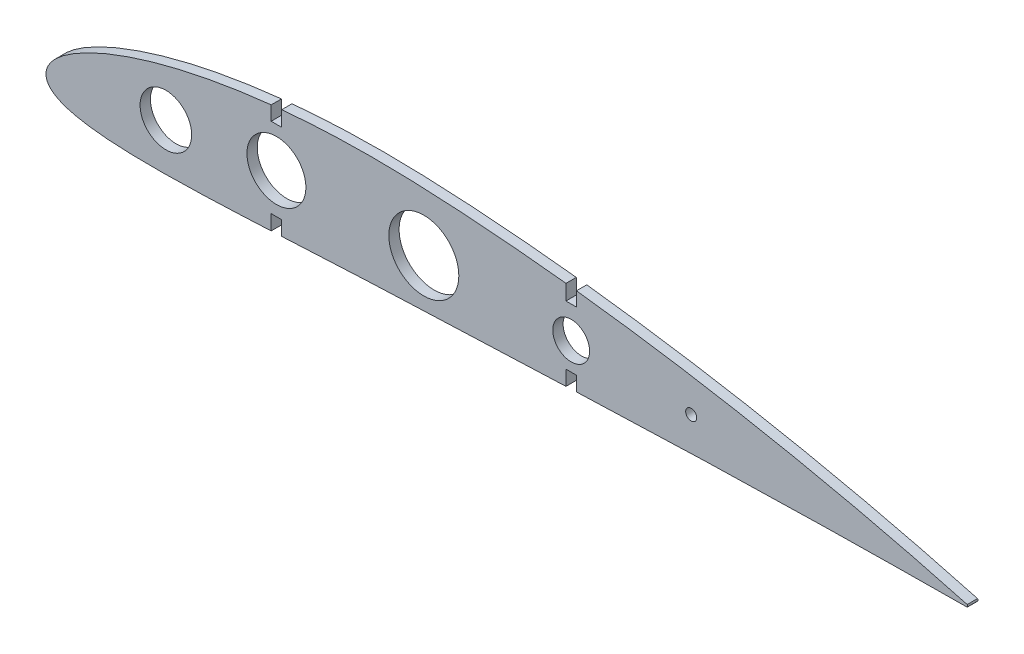
SolidWorks part; units mm, degrees
material "Фанера"
ref_plane "Front Plane" through (0, 0, 0) normal (0, 0, 1) x (1, 0, 0)
ref_plane "Top Plane" through (0, 0, 0) normal (0, 1, 0) x (1, 0, 0)
ref_plane "Right Plane" through (0, 0, 0) normal (1, 0, 0) x (0, 0, -1)
curve "Кривая5"
  spline degree 3 poles (0.048, 0.6214, 0) (0.0227, 0.3735, 0) (-0.0278, -0.1225, 0) (0.078, -0.8844, 0) (0.3497, -1.6388, 0) (0.8143, -2.3651, 0) (1.4635, -3.0393, 0) (2.291, -3.661, 0) (3.3059, -4.2358, 0) (4.5353, -4.7737, 0) (6.0297, -5.2822, 0) (7.869, -5.7653, 0) (10.1688, -6.2217, 0) (13.0754, -6.6396, 0) (16.7281, -6.993, 0) (21.19, -7.2473, 0) (26.4, -7.3766, 0) (32.1974, -7.3763, 0) (38.3978, -7.2614, 0) (44.8576, -7.0566, 0) (51.4865, -6.7865, 0) (58.231, -6.4723, 0) (65.0521, -6.1329, 0) (71.9108, -5.784, 0) (78.7714, -5.4397, 0) (85.6105, -5.111, 0) (92.4321, -4.805, 0) (99.255, -4.532, 0) (106.0974, -4.2783, 0) (112.9692, -4.0031, 0) (119.8644, -3.7232, 0) (126.7739, -3.4401, 0) (133.6816, -3.1587, 0) (140.5819, -2.8824, 0) (147.472, -2.6139, 0) (154.3526, -2.3556, 0) (161.225, -2.1094, 0) (168.0909, -1.8766, 0) (174.9516, -1.6586, 0) (181.8086, -1.4564, 0) (188.6632, -1.2704, 0) (195.5166, -1.1011, 0) (202.3695, -0.9486, 0) (209.2212, -0.8129, 0) (216.0668, -0.6936, 0) (222.8864, -0.5903, 0) (229.6176, -0.5029, 0) (236.0874, -0.4315, 0) (241.9808, -0.3765, 0) (246.559, -0.3395, 0) (249.1205, -0.3213, 0) (250, -0.315, 0) knots 0 0 0 0 0.002941 0.005884 0.009016 0.012365 0.016008 0.020037 0.024574 0.029784 0.035897 0.04324 0.052276 0.063635 0.077983 0.095698 0.11652 0.139661 0.164312 0.189919 0.216157 0.242838 0.269834 0.296993 0.324123 0.351139 0.378036 0.404946 0.431961 0.459078 0.486347 0.513641 0.540929 0.568176 0.59538 0.622543 0.649673 0.676775 0.703855 0.730919 0.757971 0.785018 0.812062 0.839103 0.866132 0.893099 0.919831 0.94581 0.969681 0.98959 1 1 1 1
curve "Кривая6"
  spline degree 3 poles (250, 0.315, 0) (249.1557, 0.545, 0) (246.7202, 1.2085, 0) (242.3913, 2.3583, 0) (236.8498, 3.7876, 0) (230.7799, 5.298, 0) (224.4559, 6.8129, 0) (218.0305, 8.2916, 0) (211.5624, 9.7197, 0) (205.0724, 11.0924, 0) (198.568, 12.4079, 0) (192.0524, 13.6653, 0) (185.5276, 14.8641, 0) (178.9953, 16.0034, 0) (172.4571, 17.0824, 0) (165.9143, 18.0998, 0) (159.3687, 19.0545, 0) (152.8218, 19.9449, 0) (146.2754, 20.7693, 0) (139.7314, 21.5257, 0) (133.1918, 22.212, 0) (126.6587, 22.8257, 0) (120.1368, 23.364, 0) (113.6286, 23.8247, 0) (107.1527, 24.2002, 0) (100.7411, 24.4984, 0) (94.4118, 24.6866, 0) (88.1559, 24.7401, 0) (81.949, 24.6588, 0) (75.7805, 24.441, 0) (69.6537, 24.0819, 0) (63.5754, 23.578, 0) (57.5552, 22.9249, 0) (51.6058, 22.1191, 0) (45.7444, 21.1566, 0) (39.9959, 20.0354, 0) (34.3979, 18.7563, 0) (29.0104, 17.3276, 0) (23.9258, 15.7719, 0) (19.2707, 14.1343, 0) (15.1791, 12.4833, 0) (11.7405, 10.8956, 0) (8.9594, 9.4296, 0) (6.7609, 8.1086, 0) (5.0337, 6.9246, 0) (3.6717, 5.8542, 0) (2.5921, 4.8713, 0) (1.7382, 3.9526, 0) (1.0699, 3.0809, 0) (0.5716, 2.2416, 0) (0.2158, 1.4308, 0) (0.1023, 0.8832, 0) (0.048, 0.6214, 0) knots 0 0 0 0 0.010162 0.029313 0.052012 0.076619 0.101948 0.127526 0.153184 0.178868 0.204558 0.230246 0.255926 0.281594 0.307246 0.332878 0.358485 0.384061 0.409603 0.435104 0.460559 0.485959 0.511303 0.536552 0.561723 0.586629 0.611085 0.635251 0.659272 0.683164 0.706922 0.730536 0.753983 0.777235 0.800246 0.822951 0.845237 0.866916 0.887662 0.906968 0.924203 0.938879 0.950932 0.960693 0.968647 0.975233 0.980795 0.985584 0.989782 0.993521 0.996902 1 1 1 1
sketch "Эскиз1" plane through (0, 0, 0) normal (0, 0, 1) x (1, 0, 0)
  line L0 (250.1305, 0) -> (250.1305, 54.8427) construction
  line L1 (0, 0) -> (0, 70.5199) construction
  line L2 (0, 0) -> (253.0634, 0) construction
  line L3 (62.5326, 62.6361) -> (62.5326, -41.5636) construction
  line L4 (142.5326, 67.9319) -> (142.5326, 25.1988) construction
  line L5 (175.0913, 63.8571) -> (175.0913, -32.3947) construction
  line L6 (32.5326, -14.3434) -> (32.5326, 29.5903) construction
  line L7 (142.5326, 21.1988) -> (142.5326, -57.0034) construction
  line L8 (61.1076, 19.4501) -> (63.9576, 19.4501)
  line L9 (61.1076, 19.4501) -> (61.1076, 23.3031)
  line L11 (63.9576, 19.4501) -> (63.9576, 23.5885)
  line L12 (61.1076, 19.4501) -> (62.5326, 23.4501) construction
  line L13 (62.5326, 23.4501) -> (63.9576, 19.4501) construction
  line L15 (61.1076, -6.3284) -> (61.1076, -2.2577)
  line L16 (61.1076, -2.2577) -> (63.9576, -2.2577)
  line L17 (63.9576, -6.1866) -> (63.9576, -2.2577)
  line L18 (62.5326, -6.2577) -> (63.9576, -2.2577) construction
  line L19 (61.1076, -2.2577) -> (62.5326, -6.2577) construction
  line L20 (141.1076, 17.1988) -> (143.9576, 17.1988)
  line L21 (141.1076, 17.1988) -> (141.1076, 21.3608)
  line L23 (143.9576, 17.1988) -> (143.9576, 21.0336)
  line L24 (141.1076, 17.1988) -> (142.5326, 21.1988) construction
  line L25 (142.5326, 21.1988) -> (143.9576, 17.1988) construction
  line L28 (141.1076, -2.8629) -> (141.1076, 1.1931)
  line L29 (141.1076, 1.1931) -> (143.9576, 1.1931)
  line L30 (143.9576, -2.7512) -> (143.9576, 1.1931)
  line L31 (142.5326, -2.8069) -> (143.9576, 1.1931) construction
  line L32 (141.1076, 1.1931) -> (142.5326, -2.8069) construction
  arc A0 (250, 0.315) -> (250, -0.315) centre (249.685, 0) cw
  circle A1 centre (62.5326, 8.5962) radius 8
  circle A2 centre (142.5326, 8.5962) radius 5
  circle A3 centre (32.5326, 5.4481) radius 7
  circle A5 centre (102.5326, 8.5962) radius 9.5
  circle A6 centre (175.0913, 7.4939) radius 1.5
  arc A7 (175.0913, 16.6448) -> (175.0913, -1.657) centre (175.0913, 7.4939) ccw
  spline S2 degree 3 poles (0.048, 0.6214) (0.0227, 0.3735) (-0.0278, -0.1225) (0.078, -0.8844) (0.3497, -1.6388) (0.8143, -2.3651) (1.4635, -3.0393) (2.291, -3.661) (3.3059, -4.2358) (4.5353, -4.7737) (6.0297, -5.2822) (7.869, -5.7653) (10.1688, -6.2217) (13.0754, -6.6396) (16.7281, -6.993) (21.19, -7.2473) (26.4, -7.3766) (32.1974, -7.3763) (38.3978, -7.2614) (44.8576, -7.0566) (51.4865, -6.7865) (56.9206, -6.5334) (60.1398, -6.3761) (61.1076, -6.3284) knots 0 0 0 0 0.002941 0.005884 0.009016 0.012365 0.016008 0.020037 0.024574 0.029784 0.035897 0.04324 0.052276 0.063635 0.077983 0.095698 0.11652 0.139661 0.164312 0.189919 0.216157 0.242838 0.254307 0.254307 0.254307 0.254307
  spline S3 degree 3 poles (250, 0.315) (249.1557, 0.545) (246.7202, 1.2085) (242.3913, 2.3583) (236.8498, 3.7876) (230.7799, 5.298) (224.4559, 6.8129) (218.0305, 8.2916) (211.5624, 9.7197) (205.0724, 11.0924) (198.568, 12.4079) (192.0524, 13.6653) (185.5276, 14.8641) (178.9953, 16.0034) (172.4571, 17.0824) (165.9143, 18.0998) (159.3687, 19.0545) (152.8218, 19.9449) (147.6839, 20.5919) (144.7288, 20.9433) (143.9576, 21.0336) knots 0 0 0 0 0.010162 0.029313 0.052012 0.076619 0.101948 0.127526 0.153184 0.178868 0.204558 0.230246 0.255926 0.281594 0.307246 0.332878 0.358485 0.384061 0.409603 0.418619 0.418619 0.418619 0.418619
  spline S4 degree 3 poles (61.1076, 23.3031) (59.9179, 23.1768) (56.7397, 22.8145) (51.6058, 22.1191) (45.7444, 21.1566) (39.9959, 20.0354) (34.3979, 18.7563) (29.0104, 17.3276) (23.9258, 15.7719) (19.2707, 14.1343) (15.1791, 12.4833) (11.7405, 10.8956) (8.9594, 9.4296) (6.7609, 8.1086) (5.0337, 6.9246) (3.6717, 5.8542) (2.5921, 4.8713) (1.7382, 3.9526) (1.0699, 3.0809) (0.5716, 2.2416) (0.2158, 1.4308) (0.1023, 0.8832) (0.048, 0.6214) knots 0.740091 0.740091 0.740091 0.740091 0.753983 0.777235 0.800246 0.822951 0.845237 0.866916 0.887662 0.906968 0.924203 0.938879 0.950932 0.960693 0.968647 0.975233 0.980795 0.985584 0.989782 0.993521 0.996902 1 1 1 1
  spline S5 degree 3 poles (63.9576, -6.1866) (64.3178, -6.1685) (66.9697, -6.0353) (71.9108, -5.784) (78.7714, -5.4397) (85.6105, -5.111) (92.4321, -4.805) (99.255, -4.532) (106.0974, -4.2783) (112.9692, -4.0031) (119.8644, -3.7232) (126.7739, -3.4401) (133.8556, -3.1516) (138.6334, -2.9604) (141.1076, -2.8629) knots 0.265565 0.265565 0.265565 0.265565 0.269834 0.296993 0.324123 0.351139 0.378036 0.404946 0.431961 0.459078 0.486347 0.513641 0.540929 0.570237 0.570237 0.570237 0.570237
  spline S6 degree 3 poles (143.9576, -2.7512) (145.1302, -2.7056) (148.5961, -2.5717) (154.3526, -2.3556) (161.225, -2.1094) (168.0909, -1.8766) (174.9516, -1.6586) (181.8086, -1.4564) (188.6632, -1.2704) (195.5166, -1.1011) (202.3695, -0.9486) (211.4992, -0.7677) (220.6031, -0.6199) (229.6176, -0.5029) (236.0874, -0.4315) (241.9808, -0.3765) (246.559, -0.3395) (249.1205, -0.3213) (250, -0.315) knots 0.58149 0.58149 0.58149 0.58149 0.59538 0.622543 0.649673 0.676775 0.703855 0.730919 0.757971 0.785018 0.812062 0.839103 0.893099 0.919831 0.94581 0.969681 0.98959 1 1 1 1
  spline S7 degree 3 poles (141.1076, 21.3608) (140.6472, 21.4126) (138.0081, 21.7065) (133.1918, 22.212) (126.6587, 22.8257) (120.1368, 23.364) (113.6286, 23.8247) (107.1527, 24.2002) (100.7411, 24.4984) (94.4118, 24.6866) (88.1559, 24.7401) (81.949, 24.6588) (75.7805, 24.441) (69.7854, 24.0896) (65.8508, 23.7665) (63.9576, 23.5885) knots 0.429724 0.429724 0.429724 0.429724 0.435104 0.460559 0.485959 0.511303 0.536552 0.561723 0.586629 0.611085 0.635251 0.659272 0.683164 0.706922 0.729004 0.729004 0.729004 0.729004
  point P22 (62.5326, 23.4501)
  point P23 (62.5326, -6.2577)
  point P26 (32.5326, 18.2506)
  point P27 (32.5326, -7.3543)
  point P30 (62.5326, 23.4501)
  point P31 (62.5326, -6.2577)
  point P40 (142.5326, 21.1988)
  point P43 (142.5326, -2.8069)
  point P53 (175.0913, 16.6448)
  point P56 (175.0913, -1.657)
  dimension "D3" = 16
  dimension "D8" = 14
  dimension "D10" = 10
  dimension "D9" = 19
  dimension "D27" = 3
  dimension "D1" = 250.1305
  dimension "D2" = 62.5326
  dimension "D4" = 80
  dimension "D5" = 75.0391
  dimension "D6" = 29.7079
  dimension "D7" = 14.8539
  dimension "D11" = 40
  dimension "D12" = 30
  dimension "D13" = 25.6049
  dimension "D14" = 12.8025
  dimension "D15" = 2.85
  dimension "D16" = 4
  dimension "D17" = 1.425
  dimension "D18" = 2.85
  dimension "D19" = 4
  dimension "D20" = 1.425
  dimension "D21" = 2.85
  dimension "D22" = 4
  dimension "D23" = 1.425
  dimension "D24" = 2.85
  dimension "D25" = 4
  dimension "D26" = 1.425
extrude "Бобышка-Вытянуть1" add sketch "Эскиз1" along normal mid plane 2.8 contours L21 S7 L11 L8 L9 S4 S2 L15 L16 L17 S5 L28 L29 L30 S6 A7 S3 L23 L20 A1 A2 A3 A5 | A7 S6 A0 S3 A6
equation "\"D2@Эскиз1\"=\"D1@Эскиз1\"/4"
equation "\"D7@Эскиз1\"=\"D6@Эскиз1\"/2"
equation "\"D5@Эскиз1\"=\"D1@Эскиз1\"*0.3"
equation "\"D14@Эскиз1\"=\"D13@Эскиз1\"/2"
equation "\"t\"= 2.85"
equation "\"D17@Эскиз1\"=\"D15@Эскиз1\"/2"
equation "\"D18@Эскиз1\"=\"t\""
equation "\"D20@Эскиз1\"=\"D18@Эскиз1\"/2"
equation "\"D21@Эскиз1\"=\"t\""
equation "\"D23@Эскиз1\"=\"D21@Эскиз1\"/2"
equation "\"D24@Эскиз1\"=\"t\""
equation "\"D26@Эскиз1\"=\"D24@Эскиз1\"/2"
